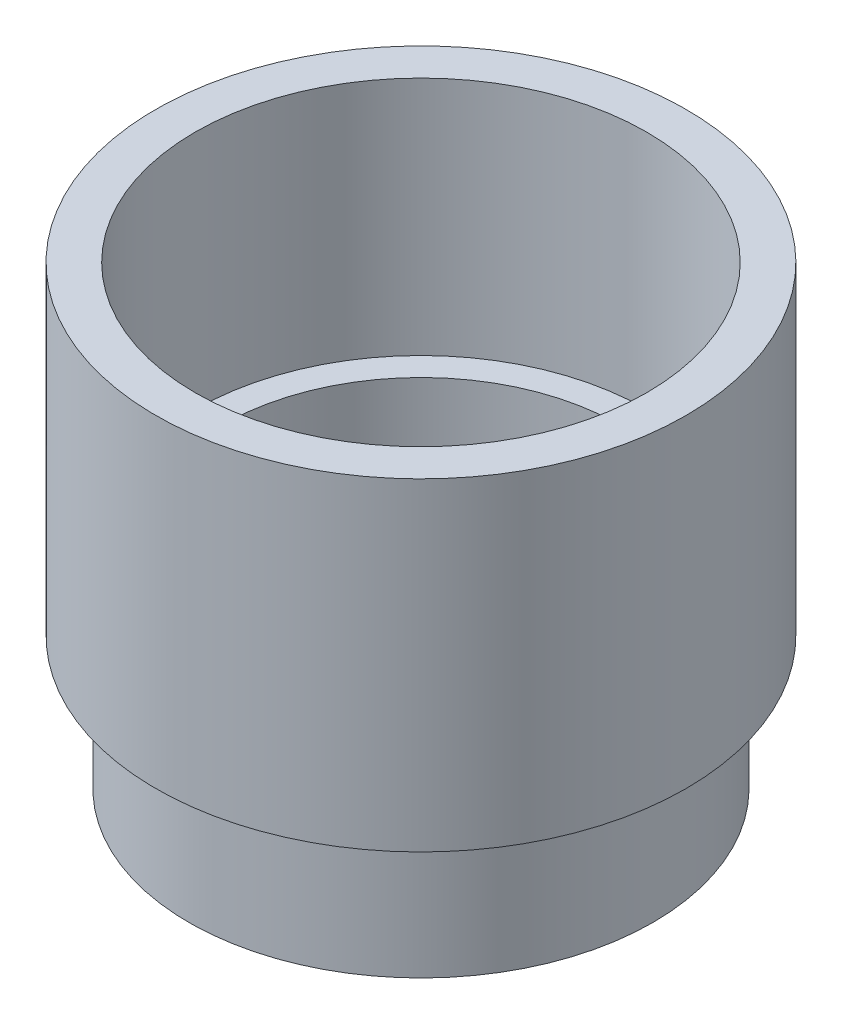
SolidWorks part; units mm, degrees
material "MC尼龙"
ref_plane "前视" through (0, 0, 0) normal (0, 0, 1) x (1, 0, 0)
ref_plane "上视" through (0, 0, 0) normal (0, 1, 0) x (1, 0, 0)
ref_plane "右视" through (0, 0, 0) normal (1, 0, 0) x (0, 0, -1)
sketch "草图1" plane through (0, 0, 0) normal (0, 0, 1) x (1, 0, 0)
  line L0 (0, -1000) -> (0, 49000) construction
  line L1 (24, 0) -> (28, 0)
  line L2 (28, 0) -> (28, 16)
  line L3 (28, 16) -> (32, 16)
  line L4 (32, 16) -> (32, 55)
  line L5 (32, 55) -> (27.25, 55)
  line L6 (24, 26) -> (24, 0)
  line L7 (27.25, 55) -> (27.25, 26)
  line L8 (27.25, 26) -> (24, 26)
  dimension "D1" = 48
  dimension "D2" = 56
  dimension "D3" = 16
  dimension "D4" = 55
  dimension "D5" = 64
  dimension "D6" = 54.5
  dimension "D7" = 10
revolve "旋转1" add sketch "草图1" angle 360 about L0
